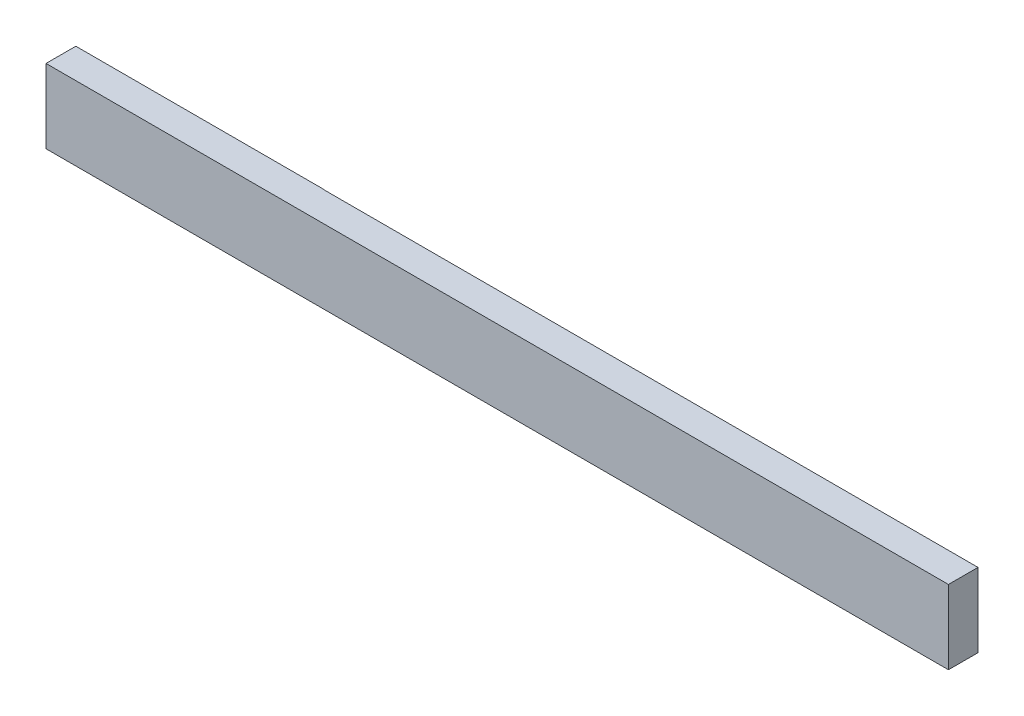
SolidWorks part; units mm, degrees
ref_plane "Front" through (0, 0, 0) normal (0, 0, 1) x (1, 0, 0)
ref_plane "Top" through (0, 0, 0) normal (0, 1, 0) x (1, 0, 0)
ref_plane "Right" through (0, 0, 0) normal (1, 0, 0) x (0, 0, -1)
sketch "Sketch1" plane through (0, 0, 0) normal (0, 1, 0) x (1, 0, 0)
  line L1 (0, 0) -> (47, 0)
  line L2 (0, 0) -> (0, 22)
  line L3 (0, 22) -> (47, 22)
  line L4 (47, 0) -> (47, 22)
  dimension "D1" = 47
  dimension "D2" = 22
extrude "Boss-Extrude1" add sketch "Sketch1" along normal blind 10
sketch "Sketch2" plane through (0, 0, 0) normal (-1, 0, 0) x (0, 0, 1)
  line L0 (-22, 0) -> (0, 0) construction
  line L1 (-4.0357, 0) -> (0, 0)
  line L2 (-4.0357, 0) -> (-4.0357, 10)
  line L3 (-4.0357, 10) -> (0, 10)
  line L4 (0, 0) -> (0, 10)
  line L5 (0, 10) -> (0, 0) construction
extrude "Boss-Extrude2" add sketch "Sketch2" along normal blind 75.1
sketch "Sketch5" plane through (0, 0, -22) normal (0, 0, -1) x (-1, 0, 0)
  line L1 (-78.5952, 37.5314) -> (41.5004, 37.5314)
  line L2 (-78.5952, 37.5314) -> (-78.5952, -29.1151)
  line L3 (-78.5952, -29.1151) -> (41.5004, -29.1151)
  line L4 (41.5004, 37.5314) -> (41.5004, -29.1151)
extrude "Cut-Extrude1" cut sketch "Sketch5" against normal blind 18
